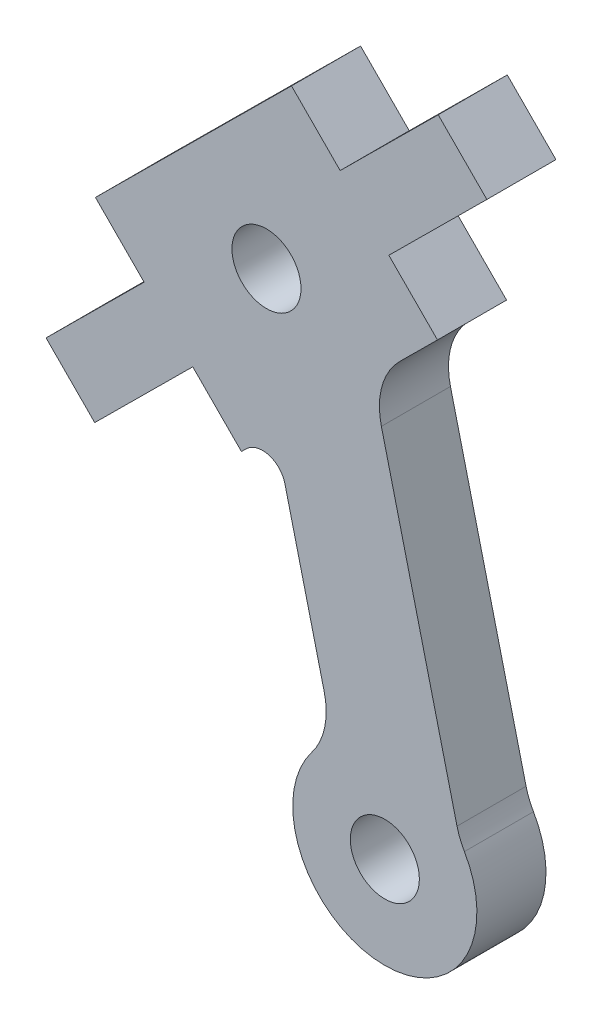
SolidWorks part; units mm, degrees
ref_plane "Plan de face" through (0, 0, 0) normal (0, 0, 1) x (1, 0, 0)
ref_plane "Plan de dessus" through (0, 0, 0) normal (0, 1, 0) x (1, 0, 0)
ref_plane "Plan de droite" through (0, 0, 0) normal (1, 0, 0) x (0, 0, -1)
sketch "Esquisse15" plane through (0, 0, 0) normal (0, 0, 1) x (1, 0, 0)
  line L0 (159.0792, -48.3653) -> (150.5631, -56.8196)
  line L1 (159.0792, -48.3653) -> (161.1927, -50.4943)
  line L2 (150.5631, -56.8196) -> (152.6767, -58.9486)
  line L3 (165.4199, -54.7523) -> (163.7832, -56.3772)
  line L4 (148.4186, -63.1758) -> (152.6767, -58.9486)
  line L5 (148.4186, -63.1758) -> (150.5322, -65.3049)
  line L6 (165.4508, -46.2671) -> (167.5644, -48.3961)
  line L7 (150.5322, -65.3049) -> (154.7903, -61.0777)
  line L8 (161.1927, -50.4943) -> (165.4508, -46.2671)
  line L9 (163.3063, -52.6233) -> (167.5644, -48.3961)
  line L10 (154.7903, -61.0777) -> (156.9039, -63.2067)
  line L11 (163.3063, -52.6233) -> (165.4199, -54.7523)
  line L12 (149.4754, -64.2403) -> (166.5076, -47.3316) construction
  line L13 (160.8096, -58.6247) -> (154.8211, -52.5924) construction
  line L14 (157.115, -62.9971) -> (156.9039, -63.2067)
  line L16 (166.2678, -72.6176) -> (162.9831, -59.2206)
  line L17 (160.4998, -70.4416) -> (158.7907, -63.4687)
  circle A0 centre (157.9915, -55.786) radius 1.5
  circle A1 centre (163.1326, -75.4261) radius 1.5
  arc A2 (159.9632, -72.9859) -> (166.5891, -73.413) centre (163.1326, -75.4261) ccw
  arc A3 (166.5891, -73.413) -> (166.2678, -72.6176) centre (169.1815, -71.9032) cw
  arc A4 (160.4998, -70.4416) -> (159.9632, -72.9859) centre (157.5861, -71.1558) cw
  arc A5 (162.9831, -59.2206) -> (163.7832, -56.3772) centre (165.8968, -58.5062) cw
  arc A6 (158.7907, -63.4687) -> (157.115, -62.9971) centre (157.8195, -63.7068) ccw
  point P23 (162.4305, -67.6426)
  point P33 (158.3698, -61.7514)
  dimension "D6" = 3
  dimension "D7" = 3
  dimension "D8" = 8
  dimension "D9" = 3
  dimension "D10" = 3
  dimension "D11" = 1
  dimension "D12" = 4.5
  dimension "D1" = 12
  dimension "D2" = 6
  dimension "D3" = 6
  dimension "D4" = 9
  dimension "D5" = 3
extrude "Boss.-Extru.15" add sketch "Esquisse15" along normal blind 3 separate body
